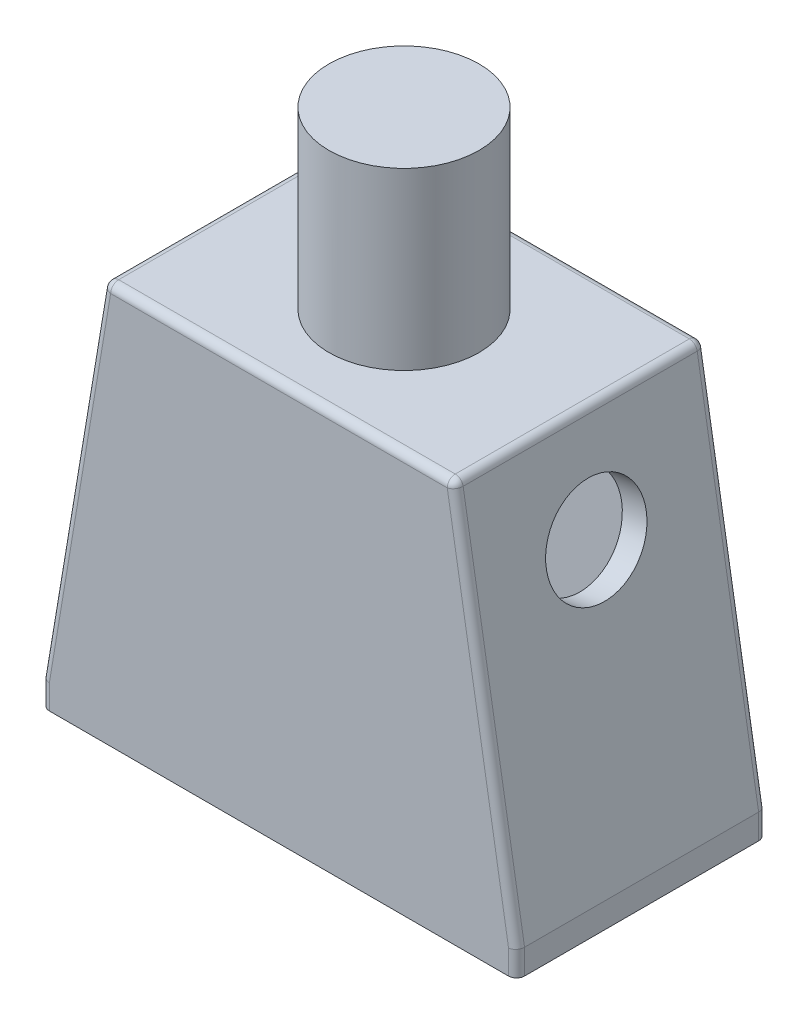
SolidWorks part; units mm, degrees
material "ABS"
ref_plane "Front Plane" through (0, 0, 0) normal (0, 0, 1) x (1, 0, 0)
ref_plane "Top Plane" through (0, 0, 0) normal (0, 1, 0) x (1, 0, 0)
ref_plane "Right Plane" through (0, 0, 0) normal (1, 0, 0) x (0, 0, -1)
sketch "Sketch1" plane through (0, 0, 0) normal (0, 0, 1) x (1, 0, 0)
  line L0 (0, 0) -> (15.0812, 0)
  line L1 (1.9844, 12.7) -> (13.0969, 12.7)
  line L2 (7.5406, 12.7) -> (7.5406, 0) construction
  line L3 (0, 0) -> (0, 0.7937)
  line L4 (15.0812, 0) -> (15.0812, 0.7938)
  line L5 (0, 0.7937) -> (1.9844, 12.7)
  line L6 (13.0969, 12.7) -> (15.0812, 0.7938)
  point P8 (7.5406, 12.7)
  dimension "D1" = 11.1125
  dimension "D2" = 12.7
  dimension "D3" = 0.7937
  dimension "D4" = 15.0812
  dimension "D5" = 9.462
  dimension "D6" = 1.9844
  dimension "D7" = 11.9062
extrude "Boss-Extrude1" add sketch "Sketch1" along normal mid plane 7.9375
fillet "Fillet1" radius 0.254 12 edges at (13.0969, 12.7, 0) (7.5406, 12.7, 3.9688) (1.9844, 12.7, 0) (7.5406, 12.7, -3.9688) (0.9922, 6.7469, -3.9688) (0.9922, 6.7469, 3.9688) (14.0891, 6.7469, -3.9688) (14.0891, 6.7469, 3.9688) (0, 0.3969, -3.9688) (15.0812, 0.3969, -3.9688) (15.0812, 0.3969, 3.9688) (0, 0.3969, 3.9688)
shell "Shell2" thickness 0.7937
sketch "Sketch2" plane through (0, 12.7, 0) normal (0, 1, 0) x (1, 0, 0)
  line L0 (2.1995, 3.7147) -> (12.8817, -3.7147) construction
  circle A0 centre (7.5406, 0) radius 2.3813
  dimension "D1" = 4.7625
extrude "Boss-Extrude2" add sketch "Sketch2" along normal blind 5.5562
sketch "Sketch4" plane through (14.8024, 2.4671, 0) normal (0.9864, 0.1644, 0) x (0, 0, -1)
  line L0 (-3.7147, -2.4793) -> (3.7147, -2.4793) construction
  line L1 (-3.9688, -1.6754) -> (-3.9688, 10.1589) construction
  circle A0 centre (0, 7.0457) radius 1.5875
  dimension "D1" = 3.175
  dimension "D2" = 9.525
  dimension "D3" = 3.9688
extrude "Cut-Extrude1" cut sketch "Sketch4" against normal blind 1.905
sketch "Sketch5" plane through (-0.1287, 0.0215, 0) normal (-0.9864, 0.1644, 0) x (0, 0, 1)
  line L0 (3.9688, 12.6383) -> (3.9688, 0.804) construction
  line L1 (3.7147, 0) -> (-3.7147, 0) construction
  circle A0 centre (0, 9.525) radius 1.5875
  dimension "D3" = 3.175
  dimension "D1" = 3.9688
  dimension "D2" = 9.525
extrude "Cut-Extrude2" cut sketch "Sketch5" against normal blind 1.905
